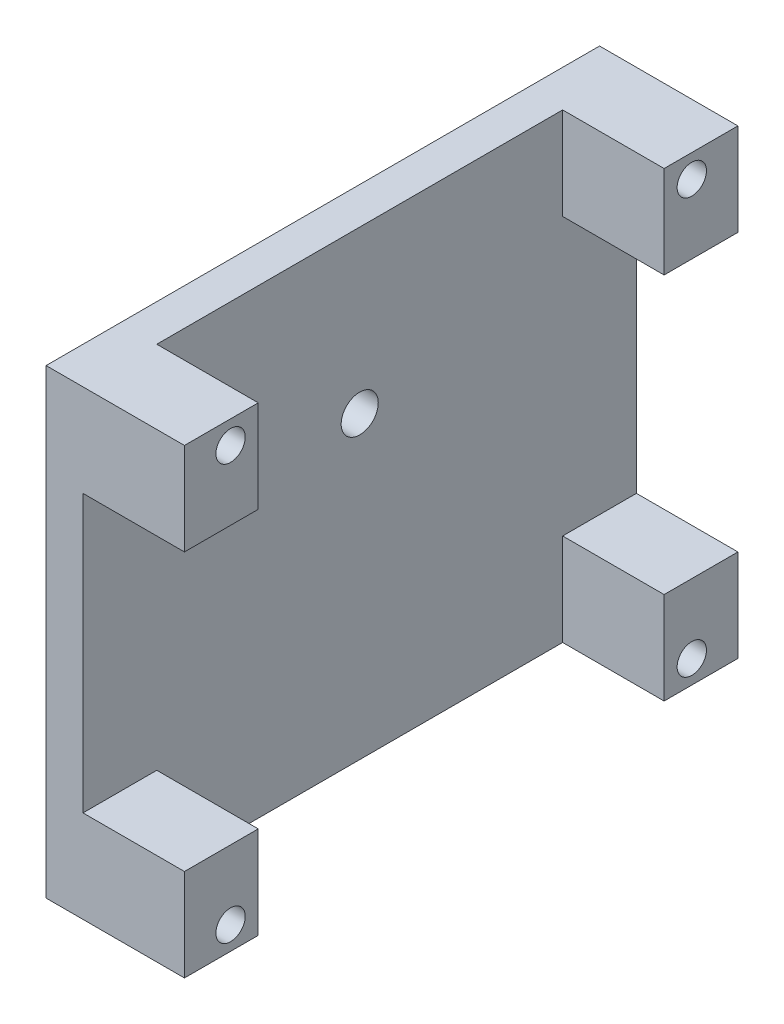
SolidWorks part; units mm, degrees
ref_plane "Front Plane" through (0, 0, 0) normal (0, 0, 1) x (1, 0, 0)
ref_plane "Top Plane" through (0, 0, 0) normal (0, 1, 0) x (1, 0, 0)
ref_plane "Right Plane" through (0, 0, 0) normal (1, 0, 0) x (0, 0, -1)
sketch "Sketch1" plane through (0, 0, 0) normal (1, 0, 0) x (0, 0, -1)
  line L1 (-38.1, -31.75) -> (38.1, -31.75)
  line L2 (-38.1, -31.75) -> (-38.1, 31.75)
  line L3 (-38.1, 31.75) -> (38.1, 31.75)
  line L4 (38.1, -31.75) -> (38.1, 31.75)
  line L5 (-38.1, -31.75) -> (38.1, 31.75) construction
  line L6 (-38.1, 31.75) -> (38.1, -31.75) construction
  point P0 (0, 0)
  dimension "D1" = 76.2
  dimension "D2" = 63.5
extrude "Boss-Extrude1" add sketch "Sketch1" along normal blind 19.05
sketch "Sketch2" plane through (19.05, 0, 0) normal (1, 0, 0) x (0, 0, -1)
  line L0 (38.1, 31.75) -> (-38.1, 31.75) construction
  line L1 (-27.94, -31.75) -> (27.94, -31.75)
  line L2 (-27.94, -31.75) -> (-27.94, 31.75)
  line L3 (-27.94, 31.75) -> (27.94, 31.75)
  line L4 (27.94, -31.75) -> (27.94, 31.75)
  line L5 (-27.94, -31.75) -> (27.94, 31.75) construction
  line L6 (-27.94, 31.75) -> (27.94, -31.75) construction
  line L7 (-38.1, 31.75) -> (-38.1, -31.75) construction
  point P0 (0, 0)
  dimension "D1" = 10.16
extrude "Cut-Extrude1" cut sketch "Sketch2" against normal blind 13.97
hole_wizard "#10-32 Tapped Hole1" positions "Sketch6" profile "Sketch5" tap size "#10-32" standard "ANSI Inch"
sketch "Sketch6" plane through (19.05, 0, 0) normal (1, 0, 0) x (0, 0, -1)
  line L0 (-27.94, 31.75) -> (-38.1, 31.75) construction
  line L2 (-38.1, 31.75) -> (-38.1, -31.75) construction
  point P0 (-31.75, 28.575)
  dimension "D1" = 6.35
  dimension "D2" = 3.175
sketch "Sketch5" plane through (19.05, 28.575, 31.75) normal (0, 1, 0) x (0, 0, -1)
  line L0 (0, 0) -> (0, 14.9293)
  line L1 (0, 14.9293) -> (2.0193, 13.716)
  line L2 (2.0193, 13.716) -> (2.0193, 0)
  line L5 (2.0193, 0) -> (0, 0)
  line L10 (0, 14.9293) -> (-2.0193, 13.716) construction
  line L11 (0, -6.35) -> (0, 107.95) construction
  dimension "Tap Drill Dia." = 4.0386
  dimension "Tap Drill Depth" = 13.716
  dimension "Drill Angle" = 118
cosmetic thread "Hole Thread2" parameters "D1"=9.652, "D2"=4.826
hole_wizard "1/4-20 Tapped Hole1" positions "Sketch4" profile "Sketch3" tap size "1/4-20" standard "ANSI Inch"
sketch "Sketch4" plane through (5.08, 0, 0) normal (1, 0, 0) x (0, 0, -1)
  circle A0 centre (-31.75, 28.575) radius 2.0193 construction
  point P0 (0, 9.525)
  dimension "D1" = 0
  dimension "D2" = 19.05
sketch "Sketch3" plane through (5.08, 9.525, 0) normal (0, 1, 0) x (0, 0, -1)
  line L0 (0, 0) -> (0, 20.5838)
  line L1 (0, 20.5838) -> (2.5527, 19.05)
  line L2 (2.5527, 19.05) -> (2.5527, 0)
  line L5 (2.5527, 0) -> (0, 0)
  line L10 (0, 20.5838) -> (-2.5527, 19.05) construction
  line L11 (0, -6.35) -> (0, 107.95) construction
  dimension "Tap Drill Dia." = 5.1054
  dimension "Tap Drill Depth" = 19.05
  dimension "Drill Angle" = 118
cosmetic thread "Hole Thread1" parameters "D1"=5.08, "D2"=6.35
pattern_linear "LPattern1" count 2 spacing 57.15 along (0, -1, 0) count 2 spacing 63.5 along (0, 0, -1) of "#10-32 Tapped Hole1"
sketch "Sketch7" plane through (19.05, 0, 0) normal (1, 0, 0) x (0, 0, -1)
  line L0 (-38.1, 31.75) -> (-38.1, -31.75) construction
  line L1 (-38.1, 19.05) -> (38.1, 19.05)
  line L2 (-38.1, 19.05) -> (-38.1, -19.05)
  line L3 (-38.1, -19.05) -> (38.1, -19.05)
  line L4 (38.1, 19.05) -> (38.1, -19.05)
  line L6 (38.1, -31.75) -> (38.1, 31.75) construction
  circle A0 centre (-31.75, 28.575) radius 2.0193 construction
  dimension "D1" = 38.1
  dimension "D2" = 9.525
  dimension "D3" = 0
  dimension "D4" = 0
extrude "Cut-Extrude2" cut sketch "Sketch7" against normal up to surface (13.97 mm away) up to face at (5.08, 9.525, -2.5527)
